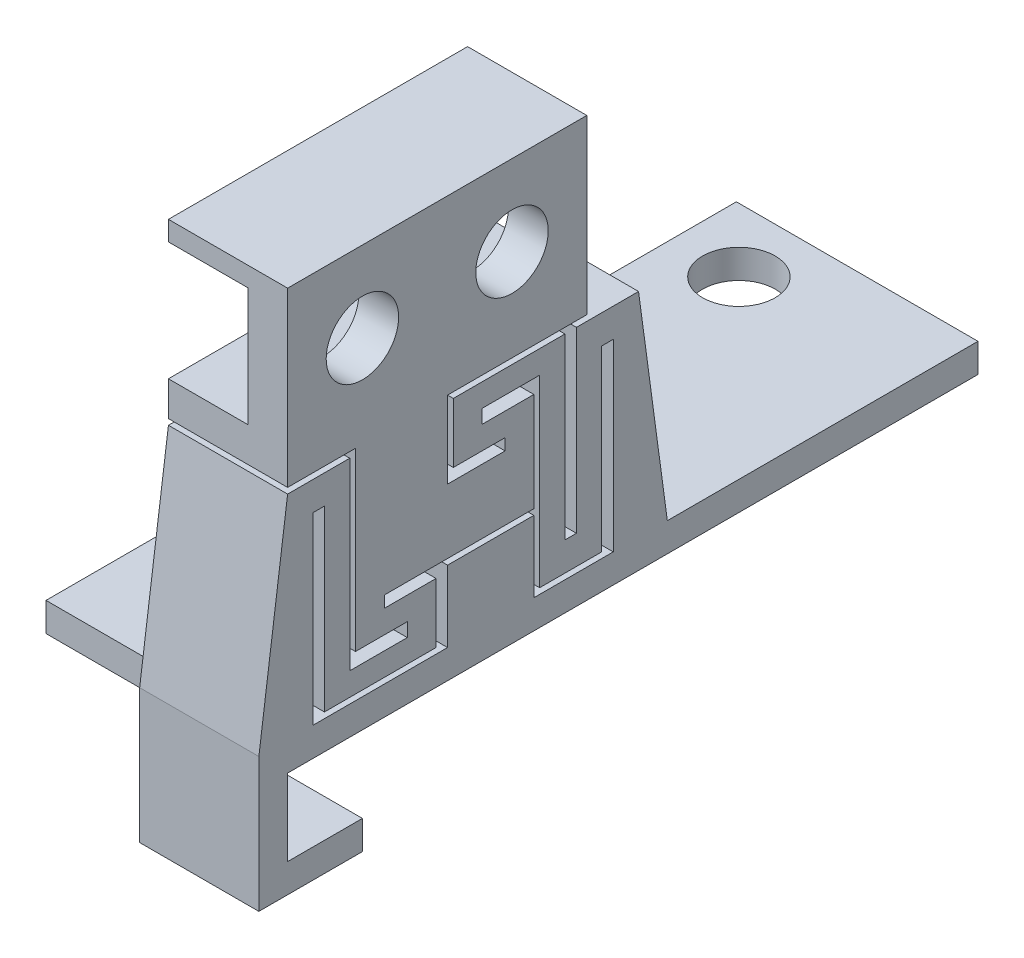
SolidWorks part; units mm, degrees
ref_plane "Front Plane" through (0, 0, 0) normal (0, 0, 1) x (1, 0, 0)
ref_plane "Top Plane" through (0, 0, 0) normal (0, 1, 0) x (1, 0, 0)
ref_plane "Right Plane" through (0, 0, 0) normal (1, 0, 0) x (0, 0, -1)
sketch "Sketch1" plane through (0, 0, 0) normal (1, 0, 0) x (0, 0, -1)
  line L0 (0, 0) -> (13, 0)
  line L1 (13, 0) -> (13, -7.5)
  line L2 (0, 0) -> (0, -7.5)
  line L3 (0, -7.5) -> (2.95, -7.5)
  line L4 (2.95, -7.5) -> (2.95, -15.15)
  line L5 (2.95, -15.15) -> (5.2, -15.15)
  line L6 (5.2, -15.15) -> (5.2, -15.75)
  line L7 (5.2, -15.75) -> (2.7, -15.75)
  line L8 (2.7, -15.75) -> (2.7, -7.75)
  line L9 (2.7, -7.75) -> (0, -7.75)
  line L10 (0, -7.75) -> (-1.25, -17)
  line L11 (13, -7.5) -> (6.95, -7.5)
  line L12 (6.95, -7.5) -> (6.95, -10.85)
  line L13 (6.95, -10.85) -> (9.45, -10.85)
  line L14 (9.45, -10.85) -> (9.45, -10.35)
  line L15 (9.45, -10.35) -> (7.2, -10.35)
  line L16 (7.2, -10.35) -> (7.2, -7.75)
  line L17 (7.2, -7.75) -> (12.05, -7.75)
  line L18 (10.7, -9.35) -> (10.7, -13.65)
  line L19 (10.7, -13.65) -> (4.2, -13.65)
  line L20 (4.2, -13.65) -> (4.2, -14.15)
  line L21 (4.2, -14.15) -> (6.45, -14.15)
  line L22 (6.45, -14.15) -> (6.45, -16.75)
  line L23 (6.45, -16.75) -> (1.6, -16.75)
  line L24 (1.6, -16.75) -> (1.6, -9)
  line L25 (1.6, -9) -> (1.1, -9)
  line L26 (1.1, -9) -> (1.1, -17)
  line L27 (1.1, -17) -> (14.15, -17)
  line L28 (10.7, -9.35) -> (8.45, -9.35)
  line L29 (8.45, -9.35) -> (8.45, -8.75)
  line L30 (8.45, -8.75) -> (10.95, -8.75)
  line L31 (10.95, -8.75) -> (10.95, -16.75)
  line L32 (12.05, -7.75) -> (12.05, -15.5)
  line L33 (12.05, -15.5) -> (12.55, -15.5)
  line L34 (12.55, -15.5) -> (12.55, -7.75)
  line L35 (12.55, -7.75) -> (15.25, -7.75)
  line L36 (10.95, -16.75) -> (13.65, -16.75)
  line L37 (13.65, -16.75) -> (13.65, -9)
  line L38 (13.65, -9) -> (14.15, -9)
  line L39 (14.15, -9) -> (14.15, -17)
  line L45 (0, -18.25) -> (16.5, -18.25)
  line L47 (16.5, -18.25) -> (16.5, -17)
  line L49 (15.25, -7.75) -> (16.5, -17)
  line L51 (-1.25, -17) -> (-1.25, -22.83)
  line L52 (-1.25, -22.83) -> (3.25, -22.83)
  line L53 (3.25, -22.83) -> (3.25, -21.58)
  line L54 (3.25, -21.58) -> (0, -21.58)
  line L55 (0, -21.58) -> (0, -18.25)
  point P49 (4.025, -16.75)
  point P53 (9.45, -10.6)
  dimension "D2" = 2.7
  dimension "D3" = 1.1
  dimension "D4" = 0.5
  dimension "D5" = 2.5
  dimension "D6" = 1.25
  dimension "D7" = 2.5
  dimension "D8" = 2.7
  dimension "D9" = 1.1
  dimension "D10" = 0.5
  dimension "D11" = 2.7
  dimension "D12" = 7.5
  dimension "D13" = 0.25
  dimension "D14" = 1.25
  dimension "D15" = 9
  dimension "D16" = 0.25
  dimension "D17" = 1.25
  dimension "D20" = 13
  dimension "D21" = 0.25
  dimension "D22" = 2.6
  dimension "D23" = 1
  dimension "D24" = 0.6
  dimension "D25" = 0.5
  dimension "D26" = 1.25
  dimension "D27" = 0.25
  dimension "D29" = 1
  dimension "D28" = 1.25
  dimension "D30" = 1.25
  dimension "D31" = 0.5
  dimension "D18" = 1.25
  dimension "D19" = 4.5
  dimension "D32" = 1.25
  dimension "D33" = 3.33
  dimension "D34" = 1.25
  dimension "D35" = 4
  dimension "D36" = 0.25
  dimension "D37" = 1.25
extrude "Boss-Extrude1" add sketch "Sketch1" along normal blind 5.18
sketch "Sketch2" plane through (0, 0, 0) normal (0, 0, 1) x (1, 0, 0)
  line L0 (5.18, 0) -> (5.18, -7.5) construction
  line L1 (5.18, -0.85) -> (1.73, -0.85)
  line L2 (5.18, -0.85) -> (5.18, -6)
  line L3 (5.18, -6) -> (1.73, -6)
  line L4 (1.73, -0.85) -> (1.73, -6)
  line L6 (5.18, -7.5) -> (0, -7.5) construction
  line L7 (5.18, 0) -> (0, 0) construction
  dimension "D1" = 3.45
  dimension "D2" = 1.5
  dimension "D3" = 0.85
extrude "Cut-Extrude1" cut sketch "Sketch2" against normal up to next
sketch "Sketch3" plane through (0, -18.25, 0) normal (0, -1, 0) x (1, 0, 0)
  line L0 (0, 1.25) -> (0, -3.25) construction
  line L1 (0, -30) -> (10.5, -30)
  line L2 (0, -30) -> (0, 0)
  line L3 (0, 0) -> (10.5, 0)
  line L4 (10.5, -30) -> (10.5, 0)
  line L6 (5.18, 0) -> (5.18, -16.5) construction
  line L7 (5.18, 1.25) -> (0, 1.25) construction
  circle A0 centre (7.62, -15.23) radius 1.575
  circle A1 centre (7.62, -27.23) radius 1.575
  dimension "D3" = 3.15
  dimension "D1" = 10.5
  dimension "D2" = 16.48
  dimension "D4" = 12
  dimension "D5" = 30
  dimension "D6" = 2.44
extrude "Boss-Extrude2" add sketch "Sketch3" against normal blind 1.25
sketch "Sketch7" plane through (0, 0, 0) normal (-1, 0, 0) x (0, 0, 1)
  line L0 (-13, 0) -> (0, 0) construction
  line L1 (0, 0) -> (0, -7.5) construction
  circle A0 centre (-3.25, -3.5) radius 1.575
  circle A1 centre (-9.75, -3.5) radius 1.575
  dimension "D1" = 3.15
  dimension "D2" = 3.5
  dimension "D3" = 3.25
  dimension "D4" = 6.5
extrude "Cut-Extrude3" cut sketch "Sketch7" against normal up to next
sketch "Sketch8" plane through (0, 0, 0) normal (-1, 0, 0) x (0, 0, 1)
  line L0 (-1.1, -17) -> (-14.15, -17) construction
  line L1 (-10.7, -17) -> (-6.95, -17)
  line L2 (-10.7, -17) -> (-10.7, -13.9)
  line L3 (-10.7, -13.9) -> (-6.95, -13.9)
  line L4 (-6.95, -17) -> (-6.95, -13.9)
  line L5 (-6.45, -14.15) -> (-6.45, -16.75) construction
  line L6 (-10.7, -13.65) -> (-4.2, -13.65) construction
  line L7 (-10.95, -16.75) -> (-10.95, -8.75) construction
  dimension "D1" = 0.5
  dimension "D2" = 0.25
  dimension "D3" = 0.25
extrude "Boss-Extrude3" add sketch "Sketch8" against normal blind 5.18
mirror "Mirror3" about plane through (0, 0, 0) normal (1, 0, 0) of bodies 109 105
delete or keep bodies "Body-Delete/Keep 1" type delete bodies bodies 109
equation "\"VerticalFlexureWidth\"= 1.1"
equation "\"VerticalFlexureGap\"= 0.5"
equation "\"VerticalDoubleFlexureWidth\"= 2 * \"VerticalFlexureWidth\" + \"VerticalFlexureGap\""
equation "\"D2@Sketch1\"=\"VerticalDoubleFlexureWidth\""
equation "\"D3@Sketch1\"=\"VerticalFlexureWidth\""
equation "\"D4@Sketch1\"=\"VerticalFlexureGap\""
equation "\"HorizontalFlexureLength\"= 2.5"
equation "\"FlexureJointWidth\"= 1.25"
equation "\"D5@Sketch1\"=\"HorizontalFlexureLength\""
equation "\"D6@Sketch1\"=\"FlexureJointWidth\""
equation "\"D7@Sketch1\"=\"HorizontalFlexureLength\""
equation "\"D8@Sketch1\"=\"VerticalDoubleFlexureWidth\""
equation "\"D9@Sketch1\"=\"VerticalFlexureWidth\""
equation "\"D10@Sketch1\"=\"VerticalFlexureGap\""
equation "\"D11@Sketch1\"=\"VerticalDoubleFlexureWidth\""
equation "\"HeadHeight\"= 7.5"
equation "\"VerticalFlexureLength\"= 9"
equation "\"MinGap\"= 0.25"
equation "\"D12@Sketch1\"=\"HeadHeight\""
equation "\"D13@Sketch1\"=\"MinGap\""
equation "\"D14@Sketch1\"=\"FlexureJointWidth\""
equation "\"D15@Sketch1\"=\"VerticalFlexureLength\""
equation "\"D16@Sketch1\"=\"MinGap\""
equation "\"D17@Sketch1\"=\"FlexureJointWidth\""
equation "\"BaseplateHeight+Tolerance\"= 3.33"
equation "\"HeadWidth\"= 13"
equation "\"D20@Sketch1\"=\"HeadWidth\""
equation "\"D21@Sketch1\"=\"MinGap\""
equation "\"D22@Sketch1\"=\"HorizontalDoubleFlexureWidth\""
equation "\"D23@Sketch1\"=\"HorizontalFlexureWidth\""
equation "\"D24@Sketch1\"=\"HorizontalFlexureGap\""
equation "\"D25@Sketch1\"=\"VerticalFlexureGap\""
equation "\"D26@Sketch1\"=\"FlexureJointWidth\""
equation "\"D27@Sketch1\"=\"MinGap\""
equation "\"D29@Sketch1\"=\"HorizontalFlexureWidth\""
equation "\"D28@Sketch1\"=\"FlexureJointWidth\""
equation "\"D30@Sketch1\"=\"FlexureJointWidth\""
equation "\"D31@Sketch1\"=\"VerticalFlexureGap\""
equation "\"D1@Boss-Extrude1\"=5.18"
equation "\"D32@Sketch1\"=\"FlexureJointWidth\""
equation "\"D18@Sketch1\"=\"FlexureJointWidth\""
equation "\"HorizontalFlexureWidth\"= 1"
equation "\"HorizontalFlexureGap\"= 0.6"
equation "\"HorizontalDoubleFlexureWidth\"= 2 * \"HorizontalFlexureWidth\" + \"HorizontalFlexureGap\""
equation "\"D34@Sketch1\"=\"FlexureJointWidth\""
equation "\"D36@Sketch1\"=\"MinGap\""
equation "\"D37@Sketch1\"=\"FlexureJointWidth\""
equation "\"D1@Boss-Extrude2\"=\"FlexureJointWidth\""
equation "\"D1@Sketch8\"=\"VerticalFlexureGap\""
equation "\"D2@Sketch8\"=\"MinGap\""
equation "\"D3@Sketch8\"=\"MinGap\""
